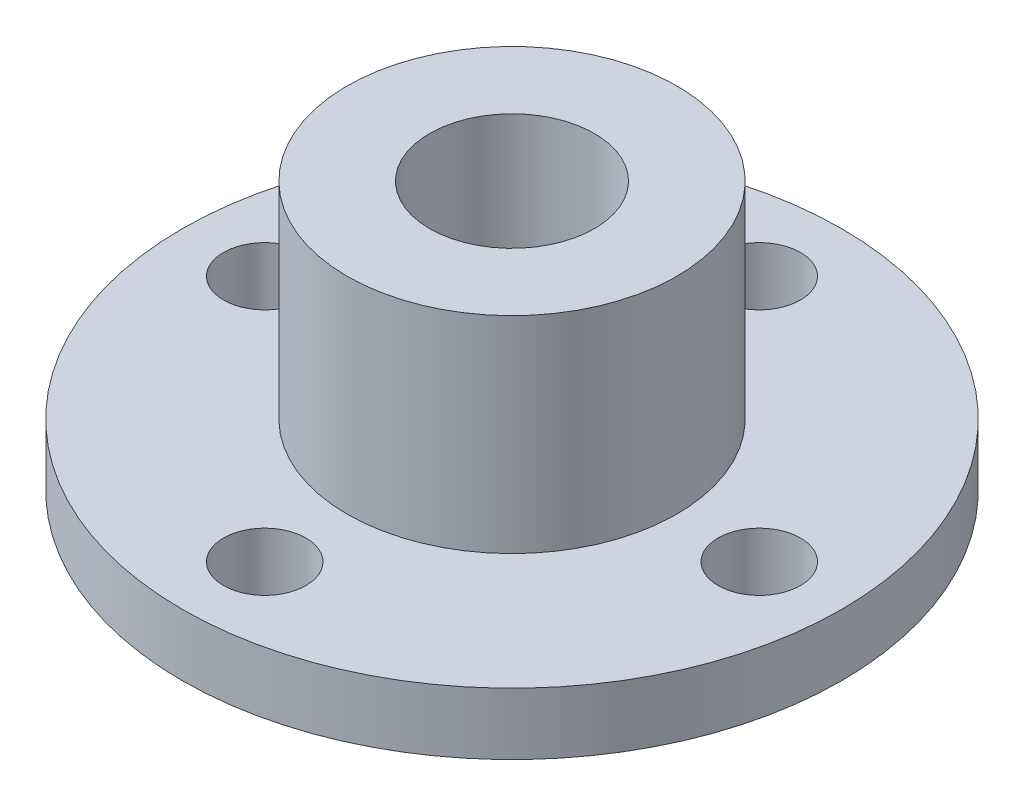
SolidWorks part; units mm, degrees
ref_plane "Front Plane" through (0, 0, 0) normal (0, 0, 1) x (1, 0, 0)
ref_plane "Top Plane" through (0, 0, 0) normal (0, 1, 0) x (1, 0, 0)
ref_plane "Right Plane" through (0, 0, 0) normal (1, 0, 0) x (0, 0, -1)
sketch "Sketch1" plane through (0, 0, 0) normal (0, 1, 0) x (1, 0, 0)
  circle A0 centre (0, 0) radius 16
extrude "Boss-Extrude1" add sketch "Sketch1" along normal blind 3
sketch "Sketch2" plane through (0, 3, 0) normal (0, 1, 0) x (1, 0, 0)
  circle A0 centre (0, 0) radius 8
extrude "Boss-Extrude2" add sketch "Sketch2" along normal blind 10
sketch "Sketch3" plane through (0, 13, 0) normal (0, 1, 0) x (1, 0, 0)
  circle A0 centre (0, 0) radius 4
extrude "Cut-Extrude1" cut sketch "Sketch3" against normal blind 10
sketch "Sketch4" plane through (0, 3, 0) normal (0, 1, 0) x (1, 0, 0)
  circle A0 centre (0, 0) radius 12 construction
  circle A1 centre (0, 12) radius 2
  circle A2 centre (-12, 0) radius 2
  circle A3 centre (0, -12) radius 2
  circle A4 centre (12, 0) radius 2
extrude "Cut-Extrude2" cut sketch "Sketch4" against normal blind 10
